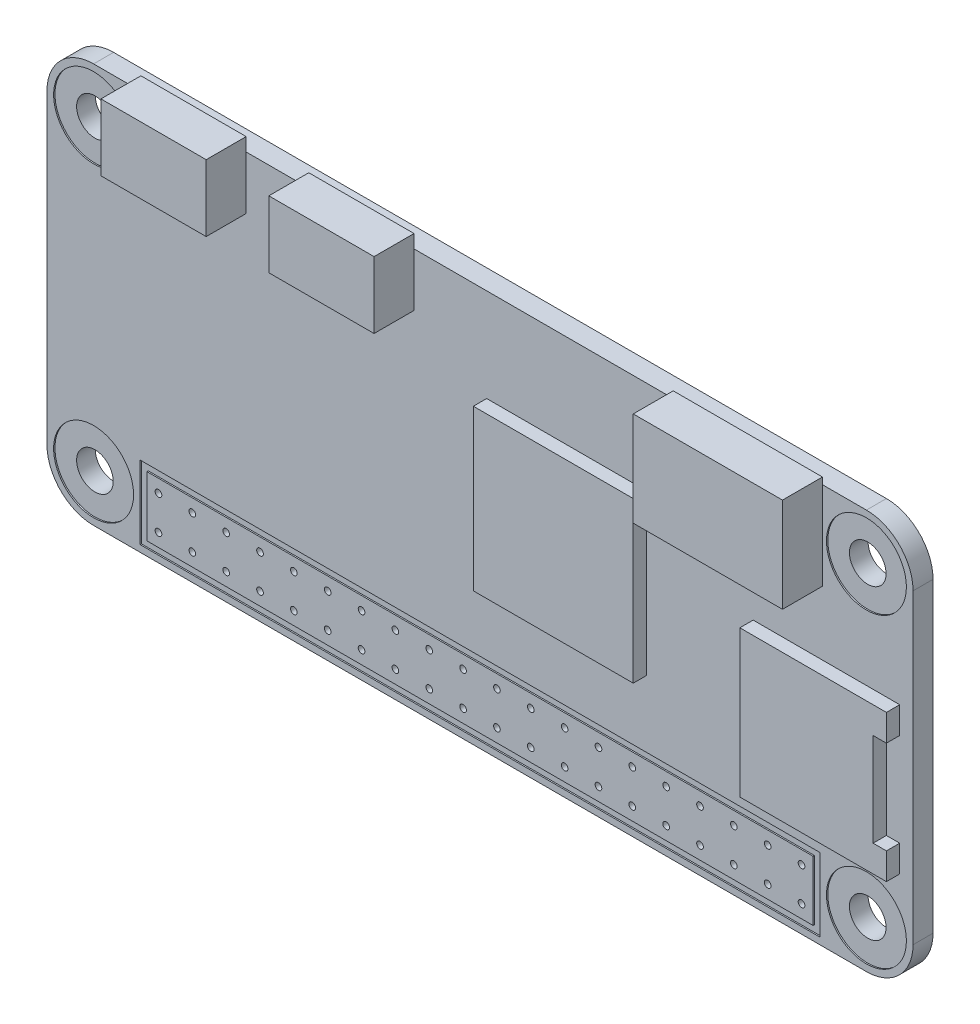
SolidWorks part; units mm, degrees
ref_plane "正面" through (0, 0, 0) normal (0, 0, 1) x (1, 0, 0)
ref_plane "平面" through (0, 0, 0) normal (0, 1, 0) x (1, 0, 0)
ref_plane "右側面" through (0, 0, 0) normal (1, 0, 0) x (0, 0, -1)
sketch "ｽｹｯﾁ1" plane through (0, 0, 0) normal (0, 0, 1) x (1, 0, 0)
  line L1 (32.5, 15) -> (-32.5, 15)
  line L2 (32.5, 15) -> (32.5, -15)
  line L3 (32.5, -15) -> (-32.5, -15)
  line L4 (-32.5, 15) -> (-32.5, -15)
  line L5 (32.5, 15) -> (-32.5, -15) construction
  line L6 (32.5, -15) -> (-32.5, 15) construction
  point P0 (0, 0)
  dimension "D1" = 30
  dimension "D2" = 65
extrude "ﾎﾞｽ - 押し出し1" add sketch "ｽｹｯﾁ1" along normal blind 1.5
fillet "ﾌｨﾚｯﾄ1" radius 3.5 4 edges at (-32.5, 15, 0.75) (-32.5, -15, 0.75) (32.5, -15, 0.75) (32.5, 15, 0.75)
sketch "ｽｹｯﾁ2" plane through (0, 0, 1.5) normal (0, 0, 1) x (1, 0, 0)
  line L1 (29, 11.5) -> (-29, 11.5) construction
  line L2 (29, 11.5) -> (29, -11.5) construction
  line L3 (29, -11.5) -> (-29, -11.5) construction
  line L4 (-29, 11.5) -> (-29, -11.5) construction
  line L5 (29, 11.5) -> (-29, -11.5) construction
  line L6 (29, -11.5) -> (-29, 11.5) construction
  circle A0 centre (29, -11.5) radius 1.375
  circle A1 centre (29, 11.5) radius 1.375
  circle A2 centre (-29, -11.5) radius 1.375
  circle A3 centre (-29, 11.5) radius 1.375
  point P0 (0, 0)
  dimension "D3" = 2.75
  dimension "D4" = 2.75
  dimension "D5" = 2.75
  dimension "D6" = 2.75
  dimension "D1" = 58
  dimension "D2" = 23
extrude "ｶｯﾄ - 押し出し1" cut sketch "ｽｹｯﾁ2" against normal blind 1.5
sketch "ｽｹｯﾁ3" plane through (0, 0, 1.5) normal (0, 0, 1) x (1, 0, 0)
  circle A0 centre (29, -11.5) radius 3
  circle A1 centre (29, 11.5) radius 3
  circle A2 centre (-29, -11.5) radius 3
  circle A3 centre (-29, 11.5) radius 3
  dimension "D1" = 6
  dimension "D2" = 6
  dimension "D3" = 6
  dimension "D4" = 6
extrude "ｶｯﾄ - 押し出し2" cut sketch "ｽｹｯﾁ3" against normal blind 0.1
sketch "ｽｹｯﾁ4" plane through (0, 0, 1.5) normal (0, 0, 1) x (1, 0, 0)
  line L0 (-29, -15) -> (29, -15) construction
  line L1 (25.5, -14.5) -> (-25.5, -14.5)
  line L2 (25.5, -14.5) -> (25.5, -9)
  line L3 (25.5, -9) -> (-25.5, -9)
  line L4 (-25.5, -14.5) -> (-25.5, -9)
  line L5 (25, -14) -> (-25, -14)
  line L6 (-25, -14) -> (-25, -9.5)
  line L7 (25, -9.5) -> (-25, -9.5)
  line L8 (25, -14) -> (25, -9.5)
  point P4 (0, -14.5)
  point P7 (0, -15)
  dimension "D1" = 51
  dimension "D2" = 0
  dimension "D3" = 5.5
  dimension "D4" = 0.5
  dimension "D5" = 0.5
sketch "ｽｹｯﾁ5" plane through (0, 0, 1.5) normal (0, 0, 1) x (1, 0, 0)
  line L0 (25.5, -14.5) -> (25.5, -9) construction
  circle A0 centre (24.13, -13.02) radius 0.25
  circle A1 centre (24.13, -10.48) radius 0.25
  point P6 (25.5, -11.75)
  dimension "D1" = 0.5
  dimension "D2" = 0.5
  dimension "D3" = 2.54
  dimension "D4" = 1.27
  dimension "D5" = 1.37
extrude "ｶｯﾄ - 押し出し3" cut sketch "ｽｹｯﾁ5" against normal up to next
pattern_linear "直線ﾊﾟﾀｰﾝ1" count 20 spacing 2.54 along (-1, 0, 0) of "ｶｯﾄ - 押し出し3"
sketch "ｽｹｯﾁ6" plane through (0, 0, 1.5) normal (0, 0, 1) x (1, 0, 0)
  line L0 (32.5, -11.5) -> (32.5, 11.5) construction
  line L1 (25.7, 8.4) -> (14.5, 8.4)
  line L2 (25.7, 8.4) -> (25.7, 15.5)
  line L3 (25.7, 15.5) -> (14.5, 15.5)
  line L4 (14.5, 8.4) -> (14.5, 15.5)
  line L5 (-4.95, 11) -> (-12.85, 11)
  line L6 (-4.95, 11) -> (-4.95, 16)
  line L7 (-4.95, 16) -> (-12.85, 16)
  line L8 (-12.85, 11) -> (-12.85, 16)
  line L9 (-17.55, 11) -> (-25.45, 11)
  line L10 (-17.55, 11) -> (-17.55, 16)
  line L11 (-17.55, 16) -> (-25.45, 16)
  line L12 (-25.45, 11) -> (-25.45, 16)
  line L13 (29, 15) -> (-29, 15) construction
  point P14 (20.1, 15.5)
  point P17 (-8.9, 16)
  point P18 (-21.5, 16)
  dimension "D1" = 12.4
  dimension "D2" = 11.2
  dimension "D3" = 7.1
  dimension "D4" = 0.5
  dimension "D5" = 41.4
  dimension "D6" = 54
  dimension "D7" = 7.9
  dimension "D8" = 7.9
  dimension "D9" = 5
  dimension "D10" = 5
  dimension "D11" = 1
  dimension "D12" = 1
extrude "ﾎﾞｽ - 押し出し3" add sketch "ｽｹｯﾁ6" along normal blind 3
sketch "ｽｹｯﾁ7" plane through (0, 0, 1.5) normal (0, 0, 1) x (1, 0, 0)
  line L0 (32.5, -11.5) -> (32.5, 11.5) construction
  line L1 (12.5, -4) -> (0.5, -4)
  line L2 (12.5, -4) -> (12.5, 8)
  line L3 (12.5, 8) -> (0.5, 8)
  line L4 (0.5, -4) -> (0.5, 8)
  line L5 (14.5, 15) -> (-4.95, 15) construction
  dimension "D1" = 12
  dimension "D2" = 12
  dimension "D3" = 20
  dimension "D4" = 7
extrude "ﾎﾞｽ - 押し出し4" add sketch "ｽｹｯﾁ7" along normal blind 1
sketch "ｽｹｯﾁ8" plane through (0, 0, 1.5) normal (0, 0, 1) x (1, 0, 0)
  line L0 (32.5, -11.5) -> (32.5, 11.5) construction
  line L1 (31.5, -7.4) -> (20.5, -7.4)
  line L2 (31.5, -7.4) -> (31.5, 3.6)
  line L3 (31.5, 3.6) -> (20.5, 3.6)
  line L4 (20.5, -7.4) -> (20.5, 3.6)
  line L6 (14.5, 15) -> (-4.95, 15) construction
  point P6 (31.5, -1.9)
  dimension "D1" = 11
  dimension "D2" = 11
  dimension "D3" = 1
  dimension "D4" = 16.9
extrude "ﾎﾞｽ - 押し出し5" add sketch "ｽｹｯﾁ8" along normal blind 1
sketch "ｽｹｯﾁ9" plane through (0, 0, 2.5) normal (0, 0, 1) x (1, 0, 0)
  line L0 (31.5, -7.4) -> (31.5, 3.6) construction
  line L1 (31.5, -5.4) -> (30.5, -5.4)
  line L2 (31.5, -5.4) -> (31.5, 1.6)
  line L3 (31.5, 1.6) -> (30.5, 1.6)
  line L4 (30.5, -5.4) -> (30.5, 1.6)
  line L5 (20.5, -7.4) -> (31.5, -7.4) construction
  line L6 (31.5, 3.6) -> (20.5, 3.6) construction
  dimension "D1" = 1
  dimension "D2" = 2
  dimension "D3" = 2
extrude "ｶｯﾄ - 押し出し4" cut sketch "ｽｹｯﾁ9" against normal blind 1
extrude "ｶｯﾄ - 押し出し5" cut sketch "ｽｹｯﾁ4" against normal blind 0.1
